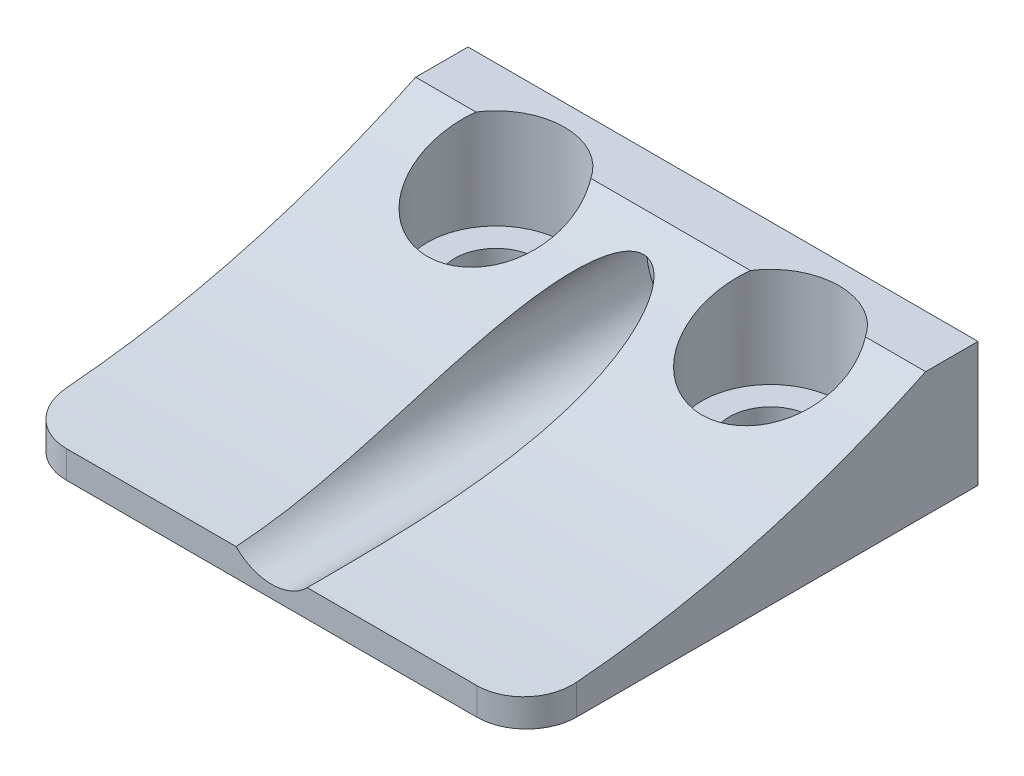
SolidWorks part; units mm, degrees
ref_plane "Front Plane" through (0, 0, 0) normal (0, 0, 1) x (1, 0, 0)
ref_plane "Top Plane" through (0, 0, 0) normal (0, 1, 0) x (1, 0, 0)
ref_plane "Right Plane" through (0, 0, 0) normal (1, 0, 0) x (0, 0, -1)
sketch "Sketch1" plane through (0, 0, 0) normal (0, 1, 0) x (1, 0, 0)
  line L1 (-10.225, -9.05) -> (10.225, -9.05)
  line L2 (-10.225, -9.05) -> (-10.225, 9.05)
  line L3 (-10.225, 9.05) -> (10.225, 9.05)
  line L4 (10.225, -9.05) -> (10.225, 9.05)
  line L5 (-10.225, -9.05) -> (10.225, 9.05) construction
  line L6 (-10.225, 9.05) -> (10.225, -9.05) construction
  point P0 (0, 0)
  dimension "D1" = 20.45
  dimension "D2" = 18.1
extrude "Boss-Extrude2" add sketch "Sketch1" along normal blind 1
sketch "Sketch3" plane through (0, 0, 0) normal (1, 0, 0) x (0, 0, -1)
  line L0 (9.05, 1) -> (9.05, 5)
  line L1 (9.05, 1) -> (3.05, 1)
  line L3 (9.05, 5) -> (7.05, 5)
  line L4 (-9.05, 1) -> (9.05, 1) construction
  line L5 (3.05, 1) -> (7.05, 5)
  dimension "D1" = 6
  dimension "D2" = 4
  dimension "D3" = 2
extrude "Boss-Extrude3" add sketch "Sketch3" along normal up to surface and the other way up to surface up to face at (10.225, 0.5, 0) other way up to face at (-10.225, 0.5, 0)
ref_plane "Plane5" through (0, 5, 0) normal (0, 1, 0) x (1, 0, 0)
sketch "Sketch4" plane through (0, 5, 0) normal (0, 1, 0) x (1, 0, 0)
  line L0 (-10.225, 3.05) -> (-10.225, 7.05) construction
  line L1 (10.225, 9.05) -> (-10.225, 9.05) construction
  line L2 (10.225, 3.05) -> (10.225, 7.05) construction
  circle A0 centre (-5.505, 5.45) radius 1.65
  circle A1 centre (5.505, 5.45) radius 1.65
  dimension "D5" = 3.3
  dimension "D6" = 3.3
  dimension "D1" = 4.72
  dimension "D2" = 3.6
  dimension "D3" = 3.6
  dimension "D4" = 4.72
extrude "Cut-Extrude1" cut sketch "Sketch4" against normal up to surface (5 mm away) up to face at (0, 0, 0)
sketch "Sketch10" plane through (0, 0, 0) normal (1, 0, 0) x (0, 0, -1)
  line L0 (7.05, 5) -> (6.95, 5)
  line L1 (-9.05, 1) -> (-9.05, 1.1)
  line L6 (-9.05, 0) -> (9.05, 0)
  line L7 (9.05, 0) -> (9.05, 5)
  line L8 (9.05, 5) -> (7.05, 5)
  line L9 (7.05, 5) -> (3.05, 1)
  line L10 (3.05, 1) -> (-9.05, 1)
  line L11 (-9.05, 1) -> (-9.05, 0)
  line L12 (-9.05, 0) -> (9.05, 0)
  line L13 (9.05, 0) -> (9.05, 5)
  line L14 (9.05, 5) -> (7.05, 5)
  line L15 (7.05, 5) -> (3.05, 1)
  line L16 (3.05, 1) -> (-9.05, 1)
  line L17 (-9.05, 1) -> (-9.05, 0)
  circle A0 centre (-10.3198, 41.0798) radius 40
  dimension "D1" = 80
  dimension "D3" = 0.1
  dimension "D4" = 0.1
  dimension "D2" = 0
extrude "Boss-Extrude5" add sketch "Sketch10" along normal up to surface and the other way up to surface
sketch "Sketch6" plane through (0, 5, 0) normal (0, 1, 0) x (1, 0, 0)
  circle A0 centre (-5.505, 5.45) radius 2.75
  circle A1 centre (5.505, 5.45) radius 2.75
  dimension "D1" = 5.5
  dimension "D2" = 5.5
extrude "Cut-Extrude2" cut sketch "Sketch6" against normal blind 4
sketch "Sketch7" plane through (0, 0, 0) normal (0, 0, 1) x (1, 0, 0)
  line L0 (3.2684, 5) -> (-3.2684, 5) construction
  line L1 (-10.225, 1) -> (-10.225, 5) construction
  circle A0 centre (0, 2.5) radius 1.15
  dimension "D3" = 2.3
  dimension "D1" = 2.5
  dimension "D2" = 10.225
extrude "Cut-Extrude3" cut sketch "Sketch7" against normal up to surface (9.05 mm away) up to face at (0, 2.5, -9.05)
sketch "Sketch8" plane through (0, 0, 0) normal (0, 0, 1) x (1, 0, 0)
  circle A0 centre (0, 2.5) radius 2
  dimension "D1" = 4
extrude "Cut-Extrude4" cut sketch "Sketch8" against normal blind 8 and the other way up to surface other way up to face at (0, 0.55, 9.05)
fillet "Fillet1" radius 2 2 edges at (-10.225, 0.55, 9.05) (10.225, 0.55, 9.05)
